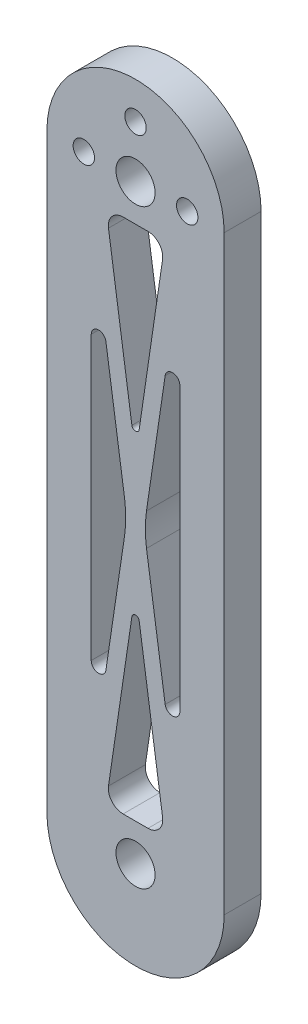
SolidWorks part; units mm, degrees
ref_plane "前视基准面" through (0, 0, 0) normal (0, 0, 1) x (1, 0, 0)
ref_plane "上视基准面" through (0, 0, 0) normal (0, 1, 0) x (1, 0, 0)
ref_plane "右视基准面" through (0, 0, 0) normal (1, 0, 0) x (0, 0, -1)
sketch "草图1" plane through (0, 0, 0) normal (0, 0, 1) x (1, 0, 0)
  line L0 (-12, 40) -> (12, 40) construction
  line L1 (-12, 40) -> (-12, -40)
  line L2 (-12, -40) -> (12, -40) construction
  line L3 (12, 40) -> (12, -40)
  line L4 (0, -40) -> (0, 40) construction
  line L5 (-12, 0) -> (12, 0) construction
  line L6 (-1.6844, 35) -> (1.6844, 35)
  line L7 (6, 19.0958) -> (6, -19.1633)
  line L8 (-1.6844, -35) -> (1.6844, -35)
  line L9 (-6, -19.1633) -> (-6, 19.0958)
  line L10 (0, -35) -> (0, 35) construction
  line L11 (-6, 0) -> (6, 0) construction
  line L12 (4.0107, 19.2419) -> (1.4808, 2.1145)
  line L13 (-1.4824, -2.2804) -> (-4.0108, -19.3101)
  line L14 (4.0108, -19.3101) -> (1.4824, -2.2804)
  line L15 (-1.4808, 2.1145) -> (-4.0107, 19.2419)
  line L16 (-3.6631, 32.709) -> (-0.4947, 11.1638)
  line L17 (3.6631, 32.709) -> (0.4947, 11.1638)
  line L18 (0.4946, -11.2589) -> (3.6629, -32.7077)
  line L19 (-0.4946, -11.2589) -> (-3.6629, -32.7077)
  arc A0 (12, 40) -> (-12, 40) centre (0, 40) ccw
  arc A1 (-12, -40) -> (12, -40) centre (0, -40) ccw
  circle A2 centre (0, 40) radius 2.65
  circle A3 centre (0, -40) radius 2.65
  circle A4 centre (7, 40) radius 1.45
  circle A5 centre (-7, 40) radius 1.45
  circle A6 centre (0, 47) radius 1.45
  arc A7 (-1.6844, -35) -> (-3.6629, -32.7077) centre (-1.6844, -33) cw
  arc A8 (3.6629, -32.7077) -> (1.6844, -35) centre (1.6844, -33) cw
  arc A9 (-3.6631, 32.709) -> (-1.6844, 35) centre (-1.6844, 33) cw
  arc A10 (3.6631, 32.709) -> (1.6844, 35) centre (1.6844, 33) ccw
  arc A11 (-0.4946, -11.2589) -> (0.4946, -11.2589) centre (0, -11.332) cw
  arc A12 (-0.4947, 11.1638) -> (0.4947, 11.1638) centre (0, 11.2366) ccw
  arc A13 (4.0108, -19.3101) -> (6, -19.1633) centre (5, -19.1633) ccw
  arc A14 (-6, -19.1633) -> (-4.0108, -19.3101) centre (-5, -19.1633) ccw
  arc A15 (-6, 19.0958) -> (-4.0107, 19.2419) centre (-5, 19.0958) cw
  arc A16 (4.0107, 19.2419) -> (6, 19.0958) centre (5, 19.0958) cw
  arc A17 (1.4824, -2.2804) -> (1.4808, 2.1145) centre (16.3198, -0.0774) cw
  arc A18 (-1.4824, -2.2804) -> (-1.4808, 2.1145) centre (-16.3198, -0.0774) ccw
  point P0 (0, 0)
  point P5 (0, 0)
  point P6 (0, 7.8)
  point P8 (-1.1562, -0.0831)
  point P9 (1.1439, 0)
  point P10 (0, -7.9103)
  point P21 (0, 0)
  point P30 (6, -35)
  point P35 (6, 35)
  point P38 (-6, 35)
  point P53 (0, -7.9103)
  point P56 (0, 7.8)
  point P69 (-1.1562, -0.0831)
  dimension "D3" = 5.3
  dimension "D4" = 5.3
  dimension "D7" = 7
  dimension "D10" = 2.9
  dimension "D11" = 2.9
  dimension "D12" = 2.9
  dimension "D13" = 2
  dimension "D14" = 0.5
  dimension "D15" = 1
  dimension "D16" = 15
  dimension "D1" = 80
  dimension "D2" = 24
  dimension "D5" = 70
  dimension "D6" = 12
  dimension "D8" = 7
  dimension "D9" = 7
extrude "凸台-拉伸1" add sketch "草图1" along normal blind 5
